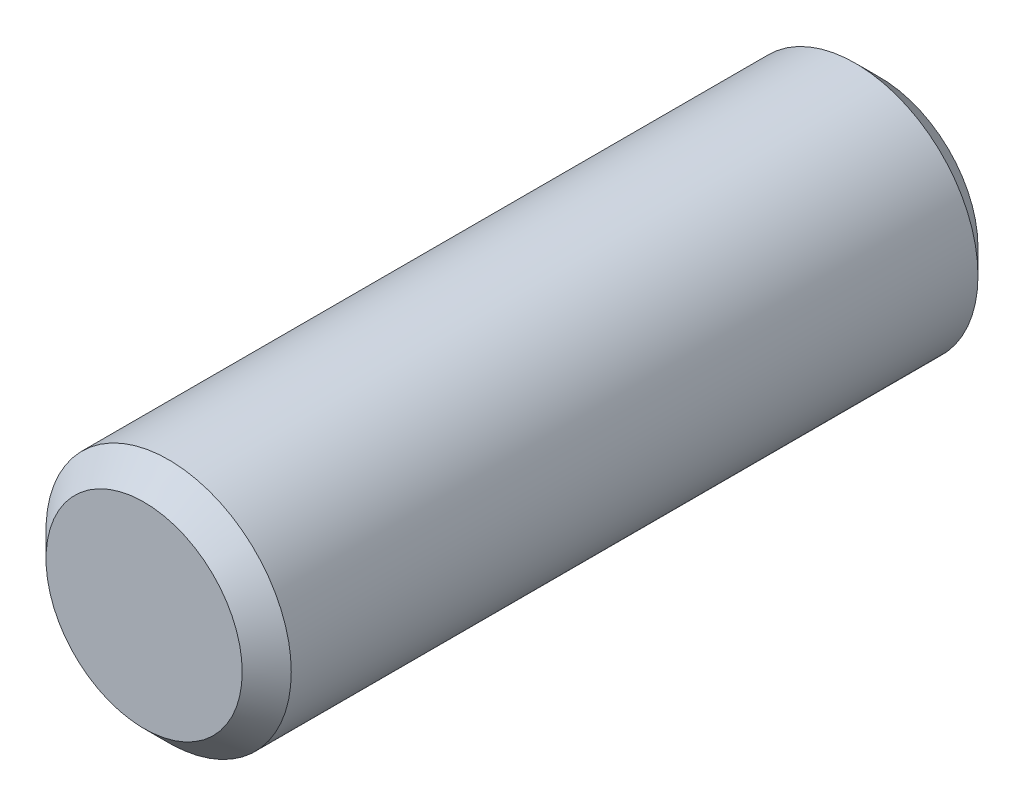
SolidWorks part; units mm, degrees
material "6061 合金"
ref_plane "前视基准面" through (0, 0, 0) normal (0, 0, 1) x (1, 0, 0)
ref_plane "上视基准面" through (0, 0, 0) normal (0, 1, 0) x (1, 0, 0)
ref_plane "右视基准面" through (0, 0, 0) normal (1, 0, 0) x (0, 0, -1)
other "Configuration Table"
sketch "草图1" plane through (0, 0, 0) normal (0, 0, 1) x (1, 0, 0)
  circle A0 centre (0, 0) radius 1
  dimension "D1" = 2
extrude "凸台-拉伸1" add sketch "草图1" along normal blind 6
chamfer "倒角1" distance 0.2 angle 45 2 edges at (1, 0, 0) (1, 0, 6)
